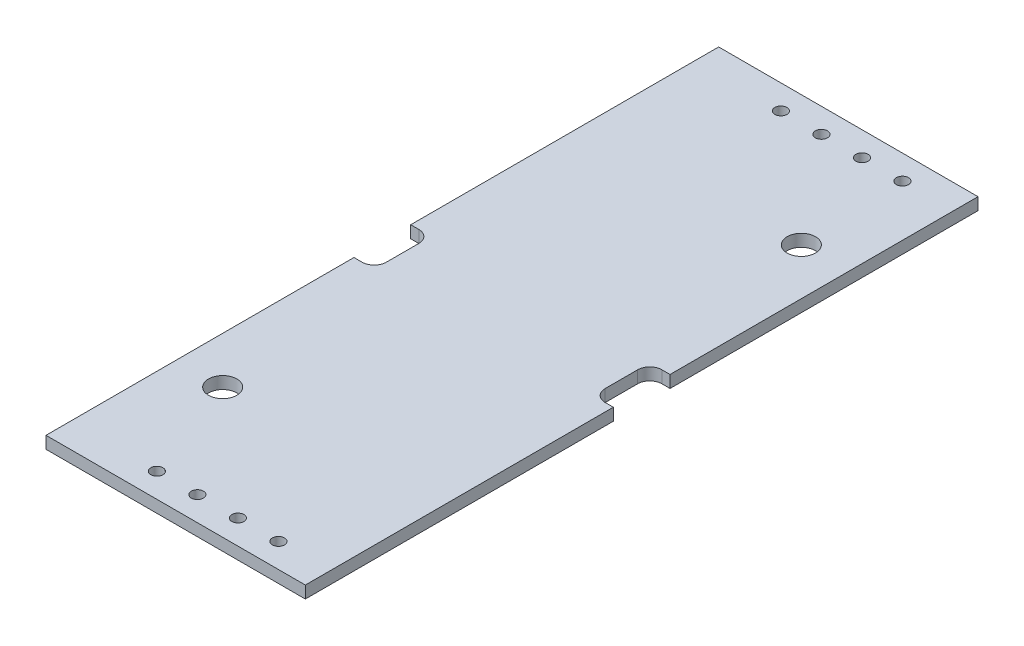
SolidWorks part; units mm, degrees
ref_plane "Спереди" through (0, 0, 0) normal (0, 0, 1) x (1, 0, 0)
ref_plane "Сверху" through (0, 0, 0) normal (0, 1, 0) x (1, 0, 0)
ref_plane "Справа" through (0, 0, 0) normal (1, 0, 0) x (0, 0, -1)
sketch "Эскиз1" plane through (0, 0, 0) normal (0, 1, 0) x (1, 0, 0)
  line L0 (-16, 41.5) -> (16, -41.5) construction
  line L1 (-16, 41.5) -> (16, 41.5)
  line L2 (-16, 41.5) -> (-16, 3.5)
  line L3 (-16, -41.5) -> (16, -41.5)
  line L4 (16, 41.5) -> (16, 3.5)
  line L5 (-16, -41.5) -> (16, 41.5) construction
  line L6 (-16, 3.5) -> (-15, 3.5)
  line L7 (-13.5, 2) -> (-13.5, -2)
  line L8 (-15, -3.5) -> (-16, -3.5)
  line L9 (16, 3.5) -> (15, 3.5)
  line L10 (13.5, 2) -> (13.5, -2)
  line L11 (15, -3.5) -> (16, -3.5)
  line L12 (-16, -3.5) -> (-16, -41.5)
  line L13 (16, -3.5) -> (16, -41.5)
  line L14 (-13.5, 0) -> (13.5, 0) construction
  arc A0 (15, 3.5) -> (13.5, 2) centre (15, 2) ccw
  arc A1 (13.5, -2) -> (15, -3.5) centre (15, -2) ccw
  arc A2 (-15, 3.5) -> (-13.5, 2) centre (-15, 2) cw
  arc A3 (-13.5, -2) -> (-15, -3.5) centre (-15, -2) cw
  point P21 (-13.5, 3.5)
  dimension "D5" = 1.5
  dimension "D1" = 32
  dimension "D2" = 83
  dimension "D3" = 38
  dimension "D4" = 2.5
extrude "Вытянуть1" add sketch "Эскиз1" along normal blind 1.5
sketch "Эскиз2" plane through (0, 1.5, 0) normal (0, 1, 0) x (1, 0, 0)
  line L0 (10.25, 41.5) -> (10.25, -41.5) construction
  line L1 (16, 41.5) -> (-16, 41.5) construction
  line L2 (-16, -41.5) -> (16, -41.5) construction
  line L3 (16, 3.5) -> (16, 41.5) construction
  line L4 (-10.25, 41.5) -> (-10.25, -41.5) construction
  line L5 (-16, 41.5) -> (-16, 3.5) construction
  line L6 (-16, 25.45) -> (16, 25.45) construction
  line L7 (-16, -25.45) -> (16, -25.45) construction
  line L8 (-16, -3.5) -> (-16, -41.5) construction
  line L9 (16, -41.5) -> (16, -3.5) construction
  line L10 (-16, 38.5) -> (16, 38.5) construction
  line L11 (-16, -38.5) -> (16, -38.5) construction
  line L12 (9.68, 41.5) -> (9.68, -41.5) construction
  line L13 (-13, 41.5) -> (-13, -41.5) construction
  line L14 (0, 41.5) -> (0, -41.5) construction
  dimension "D1" = 5.75
  dimension "D2" = 5.75
  dimension "D3" = 16.05
  dimension "D4" = 16.05
  dimension "D5" = 3
  dimension "D6" = 3
  dimension "D7" = 3
  dimension "D8" = 9.68
hole_wizard "Отверстие2" positions "Трехмерный эскиз3" profile "Эскиз5" legacy
sketch3d "Трехмерный эскиз3"
  line L0 (10.25, 1.5, -41.5) -> (10.25, 1.5, 41.5) construction
  line L1 (-16, 1.5, -25.45) -> (16, 1.5, -25.45) construction
  line L2 (-10.25, 1.5, -41.5) -> (-10.25, 1.5, 41.5) construction
  line L3 (-16, 1.5, 25.45) -> (16, 1.5, 25.45) construction
  point P0 (10.25, 1.5, -25.45)
  point P6 (-10.25, 1.5, 25.45)
sketch "Эскиз5" plane through (10.25, 1.5, -25.45) normal (1, 0, 0) x (0, 0, 1)
  line L0 (0, 0) -> (0, 1.5)
  line L1 (0, 1.5) -> (1.75, 1.5)
  line L2 (1.75, 1.5) -> (1.75, 0)
  line L3 (1.75, 0) -> (0, 0)
  line L4 (0, 110) -> (0, -10) construction
  dimension "Диаметр" = 3.5
  dimension "Глубина" = 1.5
hole_wizard "Отверстие4" positions "Трехмерный эскиз5" profile "Эскиз7" legacy
sketch3d "Трехмерный эскиз5"
  line L0 (-16, 1.5, -38.5) -> (16, 1.5, -38.5) construction
  line L1 (9.68, 1.5, -41.5) -> (9.68, 1.5, 41.5) construction
  line L2 (-16, 1.5, 38.5) -> (16, 1.5, 38.5) construction
  point P0 (9.68, 1.5, -38.5)
  point P6 (9.68, 1.5, 38.5)
sketch "Эскиз7" plane through (9.68, 1.5, -38.5) normal (1, 0, 0) x (0, 0, 1)
  line L0 (0, 0) -> (0, 1.5)
  line L1 (0, 1.5) -> (0.75, 1.5)
  line L2 (0.75, 1.5) -> (0.75, 0)
  line L3 (0.75, 0) -> (0, 0)
  line L4 (0, 110) -> (0, -10) construction
  dimension "Диаметр" = 1.5
  dimension "Глубина" = 1.5
pattern_linear "Линейный массив2" count 4 spacing 5 along (-1, 0, 0) of "Отверстие4"
